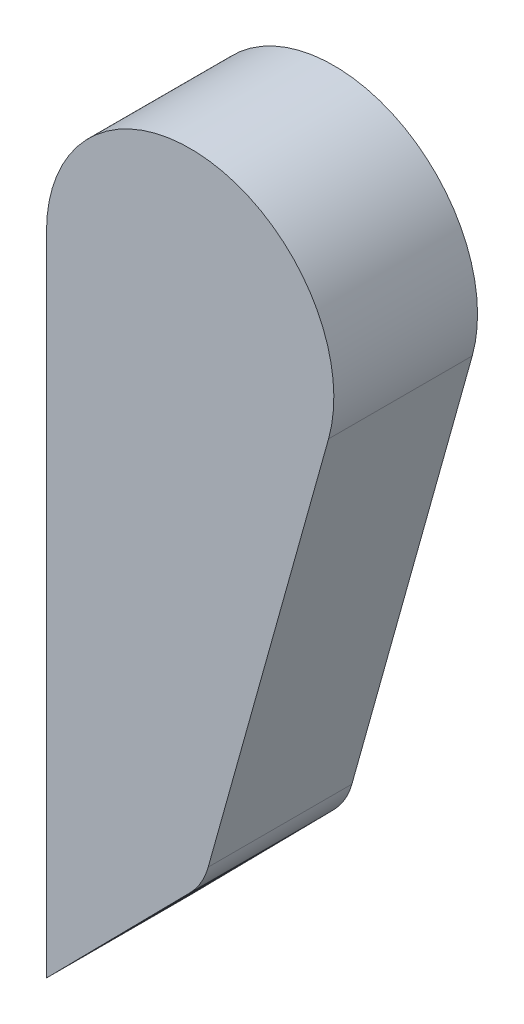
SolidWorks part; units mm, degrees
ref_plane "Front Plane" through (0, 0, 0) normal (0, 0, 1) x (1, 0, 0)
ref_plane "Top Plane" through (0, 0, 0) normal (0, 1, 0) x (1, 0, 0)
ref_plane "Right Plane" through (0, 0, 0) normal (1, 0, 0) x (0, 0, -1)
sketch "Sketch1" plane through (0, 0, 0) normal (0, 0, 1) x (1, 0, 0)
  line L0 (-20, 0) -> (-20, -90)
  line L1 (-20, -90) -> (0, -69.7092)
  line L2 (2.5097, -65.3788) -> (19.2632, -5.3788)
  arc A0 (19.2632, -5.3788) -> (-20, 0) centre (0, 0) ccw
  arc A1 (0, -69.7092) -> (2.5097, -65.3788) centre (-7.1219, -62.6894) ccw
  dimension "D1" = 10
  dimension "D3" = 20
  dimension "D2" = 90
  dimension "D4" = 60
  dimension "D5" = 20
extrude "Boss-Extrude1" add sketch "Sketch1" along normal blind 20
